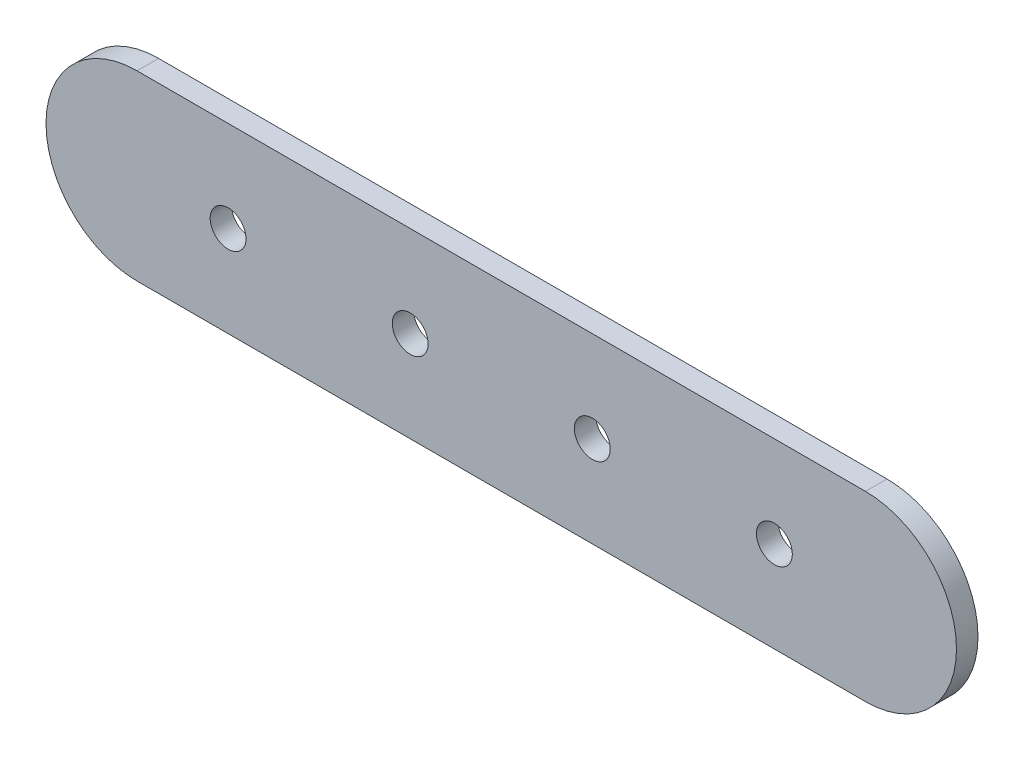
SolidWorks part; units mm, degrees
ref_plane "Front Plane" through (0, 0, 0) normal (0, 0, 1) x (1, 0, 0)
ref_plane "Top Plane" through (0, 0, 0) normal (0, 1, 0) x (1, 0, 0)
ref_plane "Right Plane" through (0, 0, 0) normal (1, 0, 0) x (0, 0, -1)
sketch "Sketch1" plane through (0, 0, 0) normal (0, 0, 1) x (1, 0, 0)
  line L0 (-494.6783, 0) -> (521.3217, 0) construction
  line L1 (-494.6783, 127) -> (521.3217, 127)
  line L2 (-494.6783, -127) -> (521.3217, -127)
  arc A0 (-494.6783, 127) -> (-494.6783, -127) centre (-494.6783, 0) ccw
  arc A1 (521.3217, -127) -> (521.3217, 127) centre (521.3217, 0) ccw
  circle A2 centre (-367.6783, 0) radius 25
  circle A3 centre (-113.6783, 0) radius 25
  circle A4 centre (140.3217, 0) radius 25
  circle A5 centre (394.3217, 0) radius 25
  point P3 (13.3217, 0)
  point P10 (-494.6783, 0)
  dimension "D3" = 50
  dimension "D1" = 254
  dimension "D2" = 1016
  dimension "D4" = 127
  dimension "D5" = 254
  dimension "D6" = 254
  dimension "D7" = 254
extrude "Boss-Extrude1" add sketch "Sketch1" along normal blind 30
